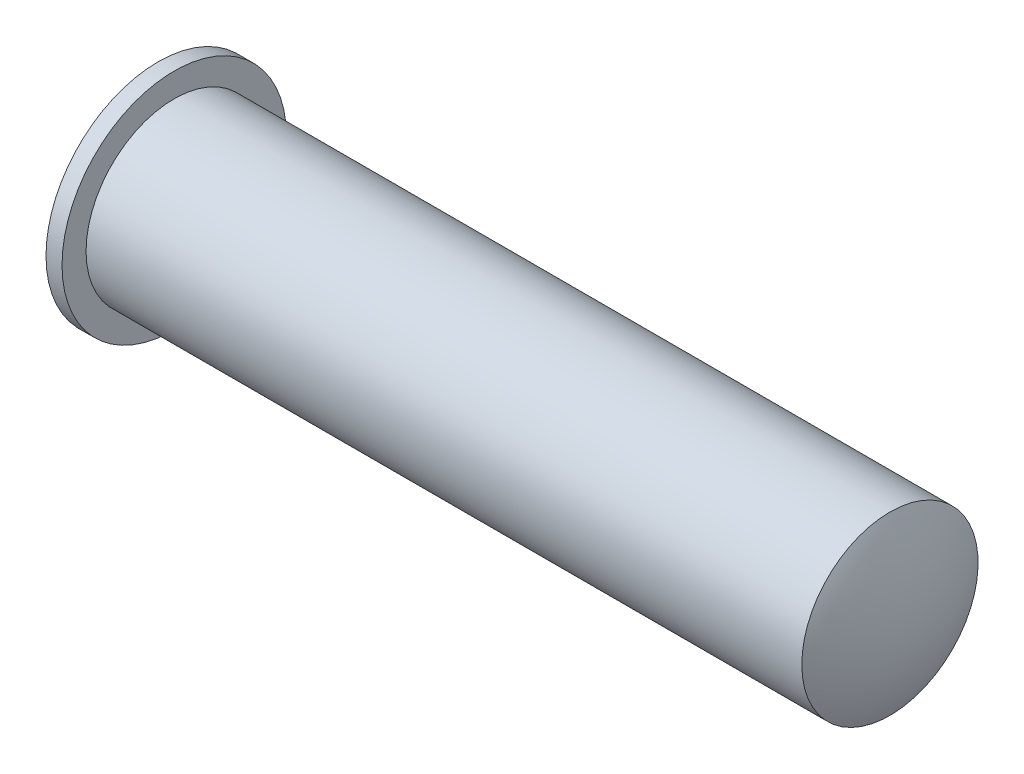
SolidWorks part; units mm, degrees
ref_plane "前视基准面" through (0, 0, 0) normal (0, 0, 1) x (1, 0, 0)
ref_plane "上视基准面" through (0, 0, 0) normal (0, 1, 0) x (1, 0, 0)
ref_plane "右视基准面" through (0, 0, 0) normal (1, 0, 0) x (0, 0, -1)
sketch "草图1" plane through (0, 0, 0) normal (0, 0, 1) x (1, 0, 0)
  line L0 (0, 7) -> (1, 7)
  line L1 (0, -55) -> (0, 55) construction
  line L2 (1, 7) -> (1, 5.5)
  line L3 (1, 5.5) -> (45.6654, 5.5)
  line L4 (55, 0) -> (-55, 0) construction
  line L5 (-2, 0) -> (47, 0) construction
  line L6 (47, 0) -> (-2, 0)
  arc A0 (45.6654, 5.5) -> (47, 0) centre (35, 0) cw
  arc A1 (0, 7) -> (-2, 0) centre (11.25, 0) ccw
  point P12 (46.6609, -3.3823)
  dimension "D1" = 49
  dimension "D6" = 12
  dimension "D7" = 13.25
  dimension "D2" = 11
  dimension "D3" = 14
  dimension "D4" = 3
  dimension "D5" = 1
revolve "旋转1" add sketch "草图1" angle 360 about L5
